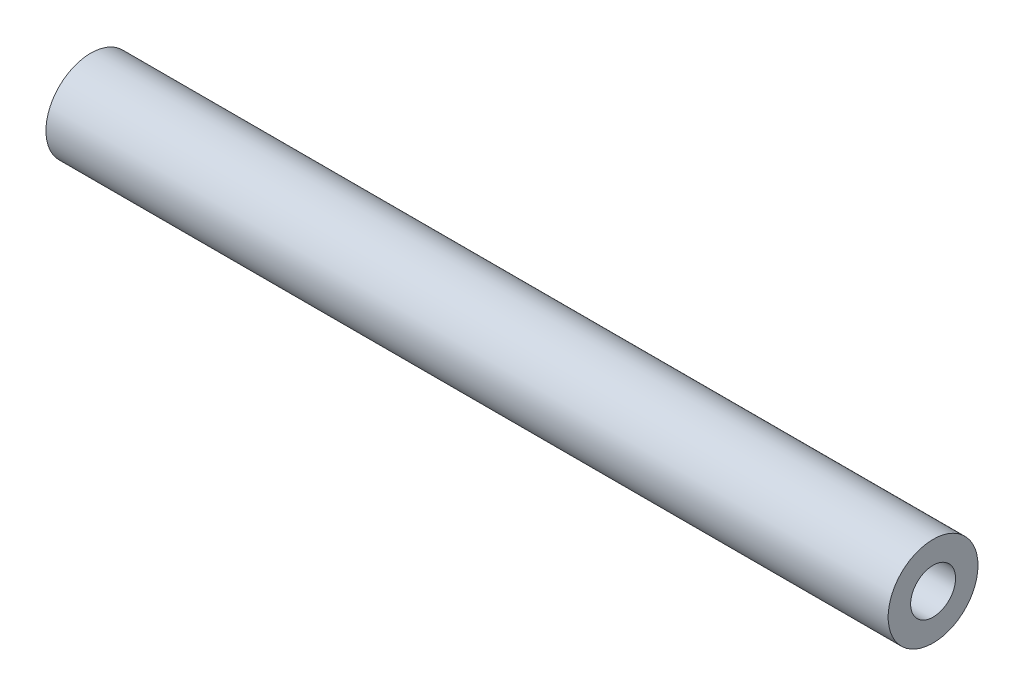
SolidWorks part; units mm, degrees
material "Oak"
ref_plane "Front" through (0, 0, 0) normal (0, 0, 1) x (1, 0, 0)
ref_plane "Top" through (0, 0, 0) normal (0, 1, 0) x (1, 0, 0)
ref_plane "Right" through (0, 0, 0) normal (1, 0, 0) x (0, 0, -1)
sketch "Sketch1" plane through (0, 0, 0) normal (1, 0, 0) x (0, 0, -1)
  circle A0 centre (0, 0) radius 4
  dimension "D1" = 8
extrude "Boss-Extrude1" add sketch "Sketch1" along normal mid plane 75
chamfer "Chamfer1" [suppressed] distance 0.5 angle 45
sketch "Sketch2" plane through (37.5, 0, 0) normal (1, 0, 0) x (0, 0, -1)
  circle A0 centre (0, 0) radius 2
  dimension "D1" = 4
extrude "Cut-Extrude1" cut sketch "Sketch2" against normal blind 15
sketch "Sketch3" plane through (-37.5, 0, 0) normal (-1, 0, 0) x (0, 0, 1)
  circle A0 centre (0, 0) radius 2
  dimension "D1" = 4
extrude "Cut-Extrude2" cut sketch "Sketch3" against normal blind 15
